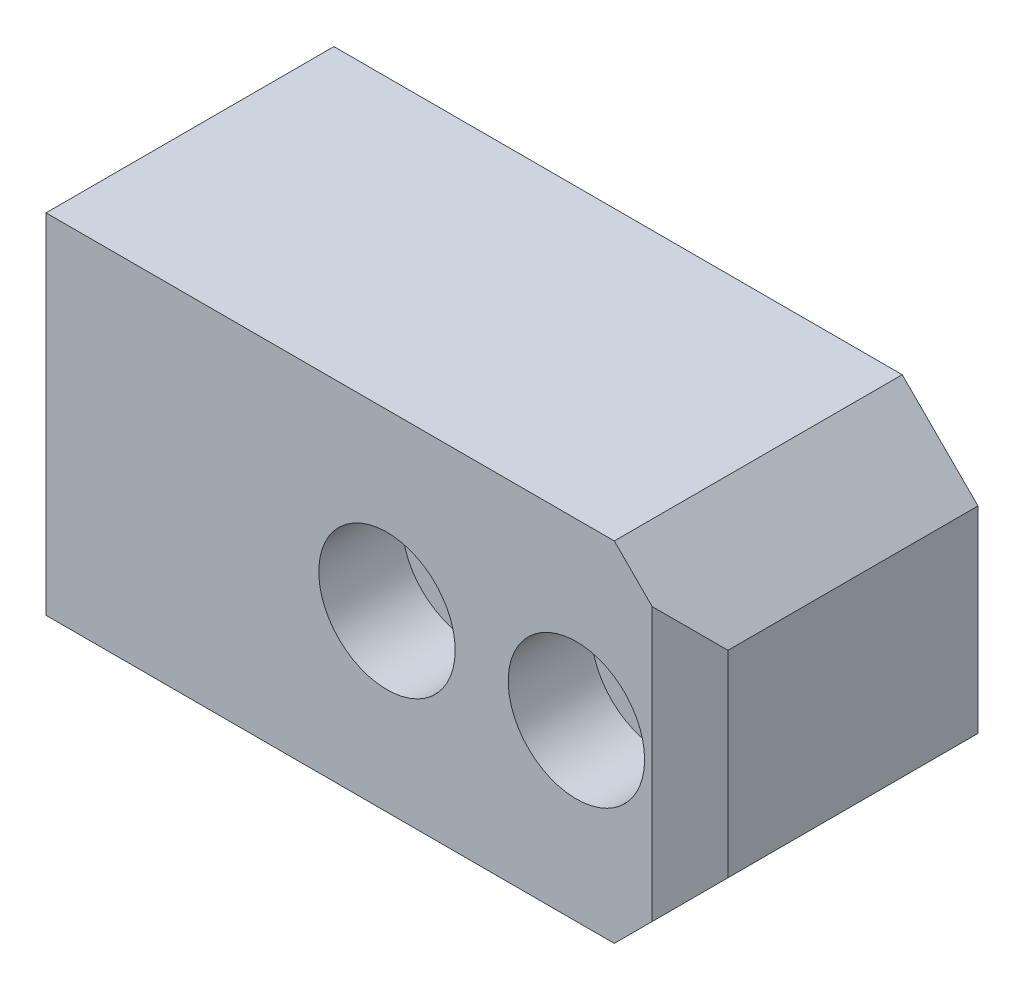
SolidWorks part; units mm, degrees
material "Q235A"
ref_plane "前视" through (0, 0, 0) normal (0, 0, 1) x (1, 0, 0)
ref_plane "上视" through (0, 0, 0) normal (0, 1, 0) x (1, 0, 0)
ref_plane "右视" through (0, 0, 0) normal (1, 0, 0) x (0, 0, -1)
sketch "草图1" plane through (0, 0, 0) normal (0, 0, 1) x (1, 0, 0)
  line L1 (42.5, -23) -> (-42.5, -23)
  line L2 (42.5, -23) -> (42.5, 23)
  line L3 (42.5, 23) -> (-42.5, 23)
  line L4 (-42.5, -23) -> (-42.5, 23)
  line L5 (42.5, -23) -> (-42.5, 23) construction
  line L6 (42.5, 23) -> (-42.5, -23) construction
  point P0 (0, 0)
  dimension "D1" = 46
  dimension "D2" = 85
extrude "凸台-拉伸1" add sketch "草图1" along normal blind 38
hole_wizard "打孔尺寸(%根据)内六角圆柱头螺钉的类型1" positions "草图3" profile "草图2" counterbore size "M10" standard "GB" end condition through all
sketch "草图3" plane through (0, 0, 38) normal (0, 0, 1) x (1, 0, 0)
  line L0 (50, 0) -> (-50, 0) construction
  line L1 (-42.5, 23) -> (-42.5, -23) construction
  point P0 (2.5, 0)
  point P4 (27.5, 0)
  dimension "D1" = 25
  dimension "D2" = 45
sketch "草图2" plane through (2.5, 0, 38) normal (1, 0, 0) x (0, -1, 0)
  line L0 (0, 0) -> (0, 38)
  line L1 (0, 38) -> (5.5, 38)
  line L3 (5.5, 38) -> (5.5, 11)
  line L4 (5.5, 11) -> (9, 11)
  line L5 (9, 11) -> (9, 0)
  line L7 (9, 0) -> (0, 0)
  line L11 (0, -6.35) -> (0, 107.95) construction
  dimension "通孔孔直径" = 11
  dimension "通孔孔深度" = 38
  dimension "柱形沉头孔直径" = 18
  dimension "柱形沉头孔深度" = 11
chamfer "倒角1" distance 10 angle 45 2 edges at (42.5, 23, 19) (42.5, -23, 19)
chamfer "倒角2" distance 5 angle 45 1 edges at (42.5, 0, 38)
